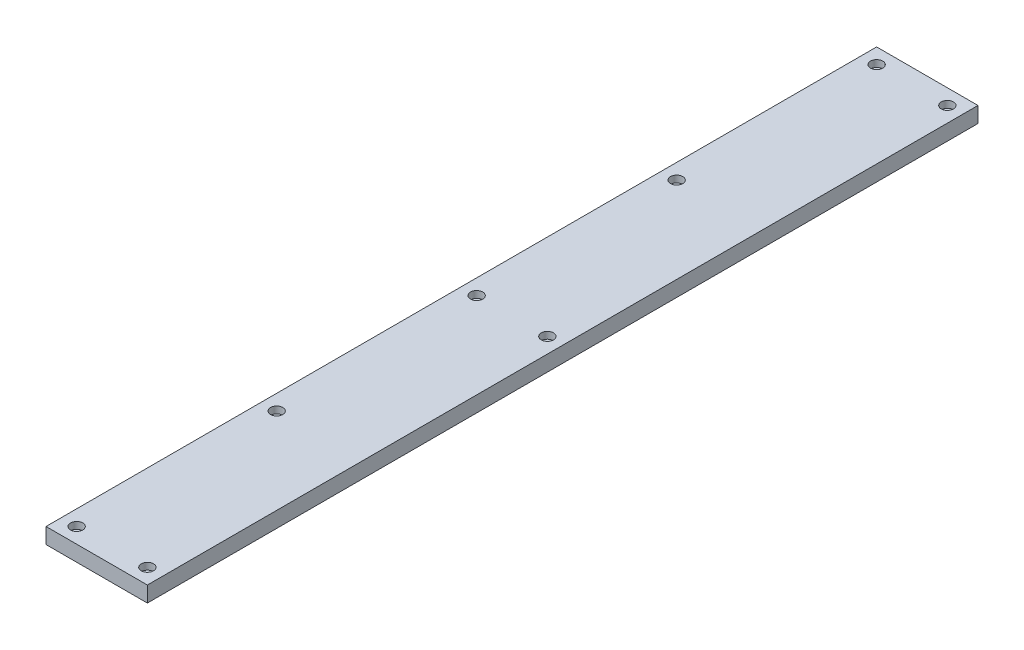
SolidWorks part; units mm, degrees
material "Pine"
ref_plane "Front Plane" through (0, 0, 0) normal (0, 0, 1) x (1, 0, 0)
ref_plane "Top Plane" through (0, 0, 0) normal (0, 1, 0) x (1, 0, 0)
ref_plane "Right Plane" through (0, 0, 0) normal (1, 0, 0) x (0, 0, -1)
sketch "Sketch1" plane through (0, 0, 0) normal (0, 1, 0) x (1, 0, 0)
  line L0 (-74.445, 610) -> (74.445, -610) construction
  line L1 (-74.445, 610) -> (74.445, 610)
  line L2 (-74.445, 610) -> (-74.445, -610)
  line L3 (-74.445, -610) -> (74.445, -610)
  line L4 (74.445, 610) -> (74.445, -610)
  dimension "D1" = 1220
  dimension "D2" = 148.89
extrude "Boss-Extrude1" add sketch "Sketch1" along normal blind 23
hole_wizard "CBORE for M8 Hex Head Bolt1" positions "Sketch2" profile "Sketch3" counterbore size "M8" standard "ISO" end condition through all
sketch "Sketch2" plane through (0, 23, 0) normal (0, 1, 0) x (1, 0, 0)
  line L0 (74.445, 610) -> (-74.445, 610) construction
  line L1 (-74.445, 610) -> (-74.445, -610) construction
  line L2 (74.445, -610) -> (74.445, 610) construction
  line L3 (-51.945, -587.5) -> (-51.945, 0) construction
  line L4 (-51.945, 0) -> (-51.945, 587.5) construction
  line L6 (-74.445, -610) -> (74.445, -610) construction
  point P0 (-51.945, 587.5)
  point P2 (51.945, 587.5)
  point P4 (-51.945, 0)
  point P6 (51.945, 0)
  point P8 (-51.945, -587.5)
  point P10 (51.945, -587.5)
  point P12 (-51.945, -293.75)
  point P14 (-51.945, 293.75)
  dimension "D1" = 22.5
  dimension "D2" = 22.5
  dimension "D3" = 22.5
  dimension "D4" = 22.5
sketch "Sketch3" plane through (-51.945, 23, -587.5) normal (1, 0, 0) x (0, 0, 1)
  line L0 (0, 0) -> (0, 23)
  line L1 (0, 23) -> (4.5, 23)
  line L3 (4.5, 23) -> (4.5, 10)
  line L4 (4.5, 10) -> (9.0055, 10)
  line L5 (9.0055, 10) -> (9.0055, 0)
  line L7 (9.0055, 0) -> (0, 0)
  line L11 (0, -6.35) -> (0, 107.95) construction
  dimension "Thru Hole Dia." = 9
  dimension "Thru Hole Depth" = 23
  dimension "C'Bore Dia." = 18.011
  dimension "C'Bore Depth" = 10
hole_wizard "CBORE for M8 Hex Head Bolt2" positions "Sketch4" profile "Sketch5" counterbore size "M8" standard "ISO"
sketch "Sketch4" plane through (0, 23, 0) normal (0, 1, 0) x (1, 0, 0)
  line L0 (-597.5, 587.5) -> (0, 587.5) construction
  line L1 (0, 587.5) -> (597.5, 587.5) construction
  point P0 (0, 587.5)
  point P2 (298.75, 587.5)
  point P4 (-298.75, 587.5)
  point P6 (-298.75, 0)
  point P8 (298.75, 0)
  point P10 (298.75, -587.5)
  point P12 (0, -587.5)
  point P14 (-298.75, -587.5)
  point P16 (0, -293.75)
  point P18 (0, 293.75)
  point P20 (-298.75, 293.75)
  point P22 (298.75, 293.75)
  point P24 (298.75, -293.75)
  point P26 (-298.75, -293.75)
  point P30 (597.5, 293.75)
  point P32 (597.5, -293.75)
  point P34 (-597.5, -587.5)
  point P37 (-597.5, 587.5)
  point P40 (0, 0)
  point P42 (597.5, -587.5)
  point P45 (-597.5, -293.75)
  point P48 (-597.5, 293.75)
sketch "Sketch5" plane through (0, 23, -587.5) normal (1, 0, 0) x (0, 0, 1)
  line L0 (0, 0) -> (0, 23)
  line L1 (0, 23) -> (4.5, 23)
  line L3 (4.5, 23) -> (4.5, 10)
  line L4 (4.5, 10) -> (9.0055, 10)
  line L5 (9.0055, 10) -> (9.0055, 0)
  line L7 (9.0055, 0) -> (0, 0)
  line L11 (0, -6.35) -> (0, 107.95) construction
  dimension "Thru Hole Dia." = 9
  dimension "Thru Hole Depth" = 23
  dimension "C'Bore Dia." = 18.011
  dimension "C'Bore Depth" = 10
